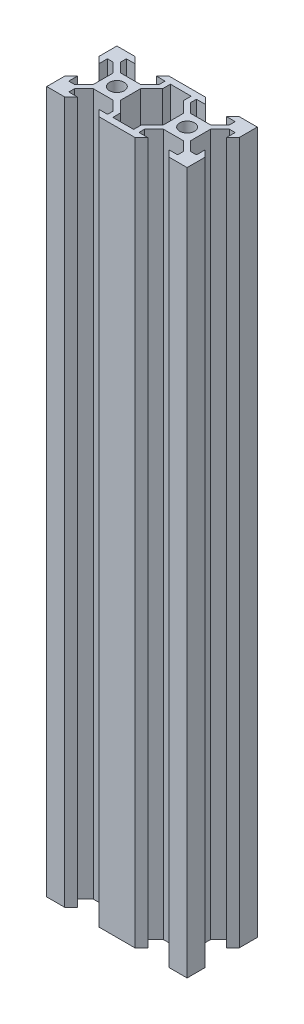
SolidWorks part; units mm, degrees
ref_plane "Front Plane" through (0, 0, 0) normal (0, 0, 1) x (1, 0, 0)
ref_plane "Top Plane" through (0, 0, 0) normal (0, 1, 0) x (1, 0, 0)
ref_plane "Right Plane" through (0, 0, 0) normal (1, 0, 0) x (0, 0, -1)
sketch "Sketch1" plane through (0, 0, 0) normal (0, 1, 0) x (1, 0, 0)
  line L0 (1.8, 15.5) -> (1.8, 13.1)
  line L1 (0, 0) -> (5.1, 0)
  line L2 (0, 0) -> (0, 5.1)
  line L3 (0, 20) -> (5.1, 20)
  line L4 (40, 0) -> (40, 5.1)
  line L5 (13.1, 18.2) -> (15.5294, 18.2)
  line L6 (38.2, 15.5) -> (38.2, 13.1)
  line L7 (35.5, 1.8) -> (33.1, 1.8)
  line L8 (1.8, 13.1) -> (0, 14.9)
  line L9 (1.8, 6.9) -> (0, 5.1)
  line L10 (6.9, 18.2) -> (5.1, 20)
  line L11 (6.9, 1.8) -> (5.1, 0)
  line L12 (33.1, 18.2) -> (34.9, 20)
  line L13 (38.2, 13.1) -> (40, 14.9)
  line L14 (38.2, 6.9) -> (40, 5.1)
  line L15 (34.9, 0) -> (33.1, 1.8)
  line L16 (10, 10) -> (40, 10) construction
  line L17 (20, 20) -> (20, 0) construction
  line L18 (13.1, 18.2) -> (14.9, 20)
  line L19 (27.0807, 18.2) -> (25.2807, 20)
  line L20 (14.9, 0) -> (13.1, 1.8)
  line L21 (25.2, 0) -> (27, 1.8)
  line L22 (20, 20) -> (20, 24.1227) construction
  line L23 (10, 24.1227) -> (0, 24.1227) construction
  line L24 (0, 24.1227) -> (0, 20) construction
  line L25 (10, 24.1227) -> (10, -5.6158) construction
  line L26 (10, 24.1227) -> (20, 24.1227) construction
  line L27 (30, 24.1227) -> (30, -5.6158) construction
  line L28 (40, 14.9) -> (40, 20)
  line L29 (38.2, 6.9) -> (38.2, 4.4706)
  line L30 (33.1, 18.2) -> (35.5, 18.2)
  line L31 (34.9, 20) -> (40, 20)
  line L32 (14.9, 20) -> (25.2807, 20)
  line L33 (1.8, 6.9) -> (1.8, 4.4706)
  line L34 (0, 14.9) -> (0, 20)
  line L35 (14.9, 0) -> (25.2, 0)
  line L36 (6.9, 1.8) -> (4.5, 1.8)
  line L37 (27, 1.8) -> (24.4705, 1.8)
  line L38 (34.9, 0) -> (40, 0)
  line L39 (4.5, 18.2) -> (6.9, 18.2)
  line L40 (0, 0) -> (0, 10) construction
  line L41 (0, 10) -> (0, 20) construction
  line L42 (5.1, 20) -> (14.9, 20) construction
  line L43 (40, 20) -> (0, 20) construction
  line L44 (4.5, 18.2) -> (15.5294, 18.2) construction
  line L45 (38.2, 6.9) -> (38.2, 13.1) construction
  line L46 (40, 14.9) -> (40, 5.1) construction
  line L47 (33.1, 1.8) -> (27, 1.8) construction
  line L48 (25.2, 0) -> (34.9, 0) construction
  line L49 (13.1, 1.8) -> (6.9, 1.8) construction
  line L50 (0, 0) -> (14.9, 0) construction
  line L51 (4.5, 18.2) -> (4.5, 15.5) construction
  line L52 (4.5, 15.5) -> (15.5, 15.5) construction
  line L53 (0, 15.5) -> (4.5, 15.5) construction
  line L54 (4.5, 15.5) -> (4.5, 20) construction
  line L55 (3.4393, 15.5) -> (4.5, 16.5607) construction
  line L56 (4.5, 16.5607) -> (7.19, 13.8706)
  line L57 (3.4393, 15.5) -> (6.1294, 12.8099)
  line L58 (4.5, 16.5607) -> (4.5, 18.2)
  line L59 (3.4393, 15.5) -> (1.8, 15.5)
  line L60 (7.1901, 6.1) -> (12.8394, 6.1)
  line L61 (1.8, 13.1) -> (1.8, 6.9) construction
  line L62 (0, 14.9) -> (0, 5.1) construction
  line L63 (6.1294, 12.8099) -> (6.1294, 7.1606)
  line L64 (12.8393, 13.8706) -> (7.19, 13.8706)
  line L65 (13.9, 7.1753) -> (13.9, 12.8247)
  line L66 (8.0827, 10.8567) -> (8.2792, 10.6602)
  line L67 (15.5294, 16.5607) -> (12.8393, 13.8706)
  line L68 (17.0395, 18.2) -> (17.0295, 15.9643)
  line L69 (13.9, 7.1753) -> (17.0295, 4.0357)
  line L70 (15.5295, 3.41) -> (12.8394, 6.1)
  line L71 (4.5, 3.4099) -> (7.1901, 6.1)
  line L72 (3.4394, 4.4706) -> (6.1294, 7.1606)
  line L73 (3.4394, 4.4706) -> (1.8, 4.4706)
  line L74 (4.5, 3.4099) -> (4.5, 1.8)
  line L75 (15.5295, 3.41) -> (15.5295, 1.8)
  line L76 (15.5294, 16.5607) -> (15.5294, 18.2)
  line L77 (17.0295, 1.8) -> (17.0295, 4.0357)
  line L78 (13.9, 12.8247) -> (17.0295, 15.9643)
  line L79 (17.0395, 18.2) -> (22.9605, 18.2)
  line L80 (16.5901, 4.4706) -> (13.9, 7.1607) [skipped]
  line L81 (16.5901, 15.5) -> (13.9, 12.81) [skipped]
  line L82 (17.0395, 18.2) -> (22.9605, 18.2) construction
  line L83 (15.5295, 1.8) -> (13.1, 1.8)
  line L84 (27.1607, 13.8706) -> (32.81, 13.8706)
  line L85 (35.5, 16.5607) -> (35.5, 18.2)
  line L86 (35.5, 16.5607) -> (32.81, 13.8706)
  line L87 (36.5607, 15.5) -> (38.2, 15.5)
  line L88 (36.5607, 15.5) -> (33.8706, 12.8099)
  line L89 (33.8706, 12.8099) -> (33.8706, 7.1606)
  line L90 (36.5606, 4.4706) -> (33.8706, 7.1606)
  line L91 (36.5606, 4.4706) -> (38.2, 4.4706)
  line L92 (35.5, 3.4099) -> (35.5, 1.8)
  line L93 (35.5, 3.4099) -> (32.8099, 6.1)
  line L94 (32.8099, 6.1) -> (27.1606, 6.1)
  line L95 (24.4705, 3.41) -> (27.1606, 6.1)
  line L96 (24.4705, 3.41) -> (24.4705, 1.8)
  line L97 (22.9705, 1.8) -> (22.9705, 4.0357)
  line L98 (26.1, 7.1753) -> (22.9705, 4.0357)
  line L99 (26.1, 7.1753) -> (26.1, 12.8247)
  line L100 (26.1, 12.8247) -> (22.9705, 15.9643)
  line L101 (24.4706, 16.5607) -> (27.1607, 13.8706)
  line L102 (24.4706, 16.5607) -> (24.4706, 18.2)
  line L103 (22.9605, 18.2) -> (22.9705, 15.9643)
  line L104 (24.4706, 18.2) -> (27.0807, 18.2)
  line L105 (24.4706, 18.2) -> (35.5, 18.2) construction
  line L106 (22.9705, 1.8) -> (17.0295, 1.8)
  circle A0 centre (10, 10) radius 2.1
  circle A1 centre (30, 10) radius 2.1
  point P67 (10.0147, 9.9853)
  point P80 (10.0147, 9.9853)
  dimension "D38" = 4.2
  dimension "D1" = 20
  dimension "D2" = 40
  dimension "D3" = 1.8
  dimension "D4" = 1.8
  dimension "D5" = 1.8
  dimension "D6" = 1.8
  dimension "D7" = 45
  dimension "D8" = 45
  dimension "D9" = 45
  dimension "D10" = 45
  dimension "D11" = 45
  dimension "D12" = 45
  dimension "D13" = 45
  dimension "D14" = 45
  dimension "D15" = 6.2
  dimension "D16" = 6.2
  dimension "D17" = 3.1
  dimension "D18" = 3.1
  dimension "D19" = 9.8
  dimension "D20" = 45
  dimension "D21" = 45
  dimension "D22" = 45
  dimension "D23" = 45
  dimension "D24" = 3.1
  dimension "D25" = 6.2
  dimension "D26" = 6.1
  dimension "D27" = 3.1
  dimension "D28" = 3.1
  dimension "D29" = 6.2
  dimension "D30" = 6.0193
  dimension "D31" = 3.1
  dimension "D32" = 4.5
  dimension "D33" = 11
  dimension "D34" = 5.1
  dimension "D35" = 4.5
  dimension "D36" = 1.5
  dimension "D37" = 45
  dimension "D39" = 10
  dimension "D40" = 10
  dimension "D41" = 6.1
  dimension "D44" = 1.5
  dimension "D42" = 4
  dimension "D43" = 4
extrude "Boss-Extrude1" add sketch "Sketch1" along normal blind 200 contours L21 L37 L96 L95 L94 L93 L92 L7 L15 L38 L4 L14 L29 L91 L90 L89 L88 L87 L6 L13 L28 L31 L12 L30 L85 L86 L84 L101 L102 L104 L19 L32 L18 L5 L76 L67 L64 L56 L58 L39 L10 L3 L34 L8 L0 L59 L57 L63 L72 L73 L33 L9 L2 L1 L11 L36 L74 L71 L60 L70 L75 L83 L20 L35 | L78 L68 L79 L103 L100 L99 L98 L97 L106 L77 L69 L65 | A1 | A0
